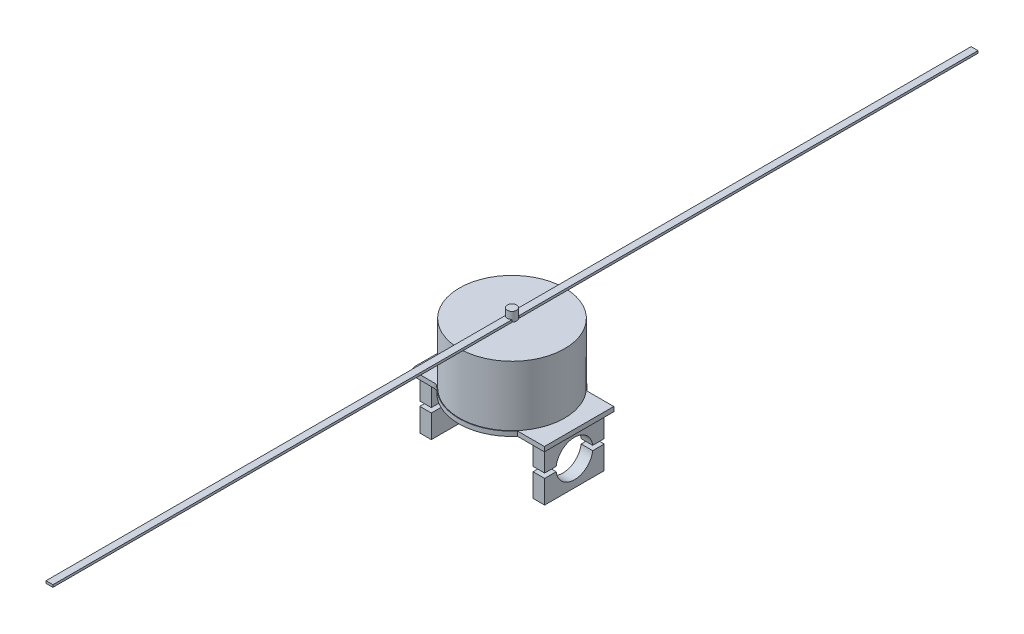
SolidWorks part; units mm, degrees
ref_plane "Front" through (0, 0, 0) normal (0, 0, 1) x (1, 0, 0)
ref_plane "Top" through (0, 0, 0) normal (0, 1, 0) x (1, 0, 0)
ref_plane "Right" through (0, 0, 0) normal (1, 0, 0) x (0, 0, -1)
sketch "Sketch1" plane through (0, 0, 0) normal (0, 1, 0) x (1, 0, 0)
  line L0 (-17.4356, 15) -> (-29, 15)
  line L1 (29, 15) -> (17.4356, 15)
  line L2 (29, 15) -> (29, -15)
  line L3 (29, -15) -> (17.4356, -15)
  line L4 (-29, 15) -> (-29, -15)
  line L5 (0, 0) -> (-29, -15) construction
  line L6 (20.429, -10.5667) -> (-29, 15) construction
  line L7 (-17.4356, -15) -> (-29, -15)
  arc A0 (-17.4356, -15) -> (17.4356, -15) centre (0, 0) ccw
  arc A1 (17.4356, 15) -> (-17.4356, 15) centre (0, 0) ccw
  dimension "D1" = 46
  dimension "D2" = 30
  dimension "D3" = 58
extrude "Boss-Extrude1" add sketch "Sketch1" along normal blind 2
ref_plane "Plane1" through (0, 0, 0) normal (-1, 0, 0) x (0, 0, 1)
sketch "Sketch2" plane through (0, 0, 0) normal (-1, 0, 0) x (0, 0, 1)
  line L0 (15.6665, -11) -> (-18.6322, -11) construction
  line L1 (-12.8869, -10) -> (-12.8869, 0)
  line L2 (-12.8869, 0) -> (12.8869, 0)
  line L3 (0, -13.0776) -> (0, 9.3484) construction
  line L4 (15.6665, -10) -> (-18.6322, -10) construction
  line L5 (-7.8869, -10) -> (-12.8869, -10)
  line L6 (12.8869, -10) -> (12.8869, 0)
  line L7 (7.8869, -10) -> (12.8869, -10)
  line L8 (7.8869, -12) -> (12.8869, -12)
  line L9 (12.8869, -12) -> (12.8869, -22)
  line L10 (-7.8869, -12) -> (-12.8869, -12)
  line L11 (-12.8869, -22) -> (12.8869, -22)
  line L12 (-12.8869, -12) -> (-12.8869, -22)
  line L13 (-15, 0) -> (15, 0) construction
  arc A0 (-7.8869, -10) -> (7.8869, -10) centre (0, -11) cw
  arc A1 (-7.8869, -12) -> (7.8869, -12) centre (0, -11) ccw
  point P14 (0, 0)
  point P21 (0, -22)
  dimension "D2" = 7.95
  dimension "D3" = 22
  dimension "D4" = 5
  dimension "D1" = 1
extrude "Boss-Extrude2" add sketch "Sketch2" against normal mid plane 54 separate body
sketch "Sketch4" plane through (0, 0, -12.8869) normal (0, 0, -1) x (-1, 0, 0)
  line L1 (-22, 0) -> (22, 0)
  line L2 (-22, 0) -> (-22, -31.6216)
  line L3 (-22, -31.6216) -> (22, -31.6216)
  line L4 (22, 0) -> (22, -31.6216)
  line L5 (-27, 0) -> (-27, -10) construction
  line L6 (27, 0) -> (27, -10) construction
  line L7 (-17.4356, 0) -> (17.4356, 0) construction
  dimension "D1" = 5
  dimension "D2" = 5
extrude "Cut-Extrude1" cut sketch "Sketch4" against normal through all
sketch "Sketch5" plane through (0, 2, 0) normal (0, 1, 0) x (1, 0, 0)
  circle A0 centre (0, 0) radius 16 construction
  circle A1 centre (0, 16) radius 1.25
  circle A2 centre (16, 0) radius 1.25
  circle A3 centre (0, -16) radius 1.25
  circle A4 centre (-16, 0) radius 1.25
  point P14 (0, 0)
  dimension "D1" = 32
  dimension "D2" = 2.5
  dimension "D3" = 4
extrude "Cut-Extrude2" cut sketch "Sketch5" against normal through all contours A4 | A1 | A2 | A3
sketch "Sketch6" plane through (0, 2, 0) normal (0, 1, 0) x (1, 0, 0)
  circle A0 centre (0, 0) radius 22.75
  dimension "D1" = 45.5
extrude "Boss-Extrude3" add sketch "Sketch6" along normal blind 26 separate body
sketch "Sketch7" plane through (0, 28, 0) normal (0, 1, 0) x (1, 0, 0)
  circle A0 centre (0, 0) radius 2
  dimension "D1" = 4
extrude "Boss-Extrude4" add sketch "Sketch7" along normal blind 4
fillet "Fillet1" radius 2 4 edges at (-17.4356, 1, -15) (-17.4356, 1, 15) (-29, 1, -15) (-29, 1, 15)
sketch "Sketch8" plane through (0, 28, 0) normal (0, 1, 0) x (1, 0, 0)
  line L0 (-1.5, -200) -> (-1.5, -1.3229)
  line L1 (200, 1.5) -> (1.3229, 1.5)
  line L2 (200, 1.5) -> (200, -1.5)
  line L3 (200, -1.5) -> (1.3229, -1.5)
  line L5 (200, 1.5) -> (-200, -1.5) construction
  line L6 (200, -1.5) -> (-200, 1.5) construction
  line L7 (1.5, -200) -> (1.5, -1.3229)
  line L8 (1.5, -200) -> (-1.5, -200)
  line L9 (-200, 1.5) -> (-1.3229, 1.5)
  line L10 (-200, -1.5) -> (-1.3229, -1.5)
  line L11 (-200, -1.5) -> (-200, 1.5)
  line L12 (1.5, 200) -> (1.5, 1.3229)
  line L13 (-1.5, 200) -> (-1.5, 1.3229)
  line L14 (-1.5, 200) -> (1.5, 200)
  circle A0 centre (0, 0) radius 2 construction
  circle A1 centre (0, 0) radius 2
  point P2 (0, 0)
  point P26 (0, 0)
  circle M5 centre (0, 0) radius 2
  circle M6 centre (0, 0) radius 22.75
  dimension "D1" = 3
  dimension "D2" = 200
  dimension "D3" = 4
extrude "Boss-Extrude5" add sketch "Sketch8" along normal blind 1 separate body contours L10 L0 L7 L3 M6 M5 | L13 L9 L1 L12 M6 M5 | L8 L7 L0 M6 | L14 L13 L12 M6 | A1
sketch "Sketch9" plane through (0, 32, 0) normal (0, 1, 0) x (1, 0, 0)
  circle A0 centre (0, 0) radius 200
  dimension "D1" = 400
